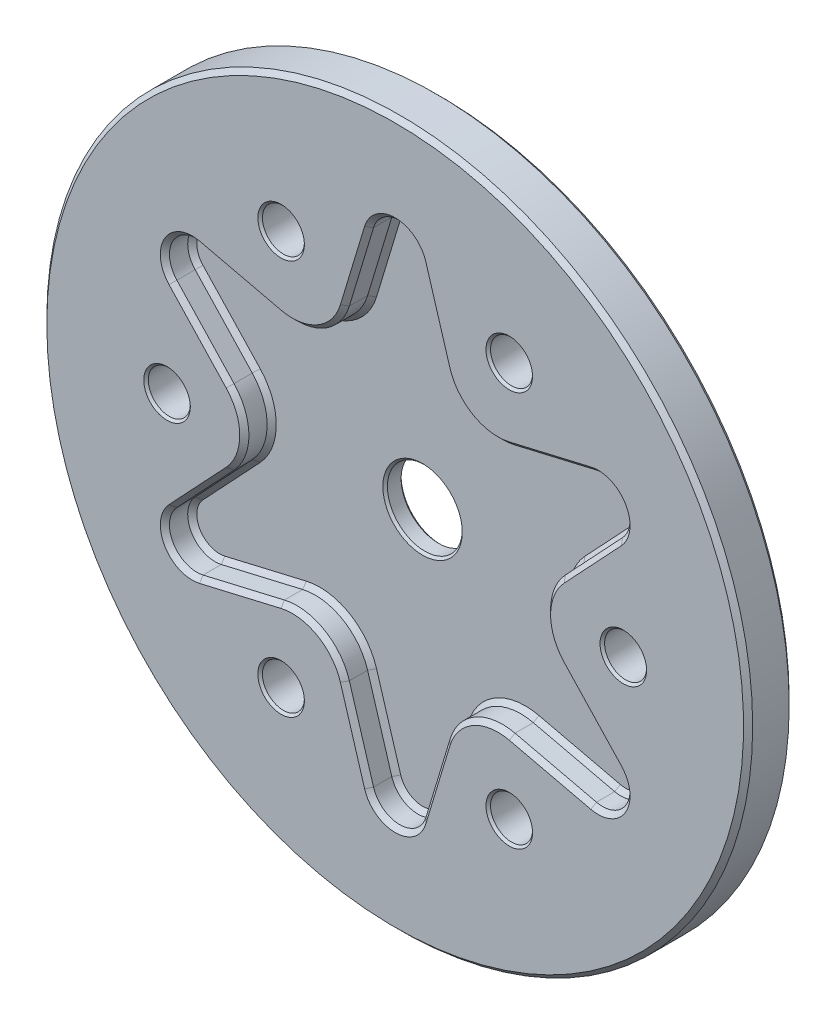
SolidWorks part; units mm, degrees
ref_plane "Front Plane" through (0, 0, 0) normal (0, 0, 1) x (1, 0, 0)
ref_plane "Top Plane" through (0, 0, 0) normal (0, 1, 0) x (1, 0, 0)
ref_plane "Right Plane" through (0, 0, 0) normal (1, 0, 0) x (0, 0, -1)
sketch "Sketch1" plane through (0, 0, 0) normal (0, 1, 0) x (1, 0, 0)
  line L0 (0, 0) -> (0, 5)
  line L4 (-38.675, 0) -> (-38.675, 5)
  line L5 (0, 5) -> (-38.675, 5)
  line L9 (-38.675, 0) -> (0, 0)
  dimension "D2" = 5
  dimension "D5" = 38.675
revolve "Revolve1" add sketch "Sketch1" angle 360 about L0
sketch "Sketch3" plane through (0, 0, 0) normal (0, 0, -1) x (-1, 0, 0)
  line L0 (25, 0) -> (-25, 0) construction
  circle A0 centre (0, 0) radius 4.1
  circle A3 centre (-12.5, 21.6506) radius 2.3
  circle A4 centre (12.5, 21.6506) radius 2.3
  circle A5 centre (25, 0) radius 2.3
  circle A6 centre (12.5, -21.6506) radius 2.3
  circle A7 centre (-12.5, -21.6506) radius 2.3
  circle A8 centre (-25, 0) radius 2.3
  point P0 (0, 0)
  dimension "D1" = 8.2
  dimension "D2" = 4.6
  dimension "D3" = 25
  dimension "D4" = 6
extrude "Cut-Extrude4" cut sketch "Sketch3" along normal through all
chamfer "Chamfer1" distance 0.5 angle 45 2 edges at (38.675, 0, 0) (38.675, 0, -5)
sketch "Sketch14" plane through (0, 0, 0) normal (0, 0, 1) x (1, 0, 0)
  line L0 (-2.8716, 26.5434) -> (-5.5228, 17.7764)
  line L1 (2.8716, 26.5434) -> (5.5228, 17.7764)
  line L2 (0, 0) -> (-12.5, 21.6506) construction
  line L3 (0, 0) -> (12.5, 21.6506) construction
  line L4 (0, 28.675) -> (0, 0) construction
  line L5 (21.5514, 15.7585) -> (12.6334, 13.671)
  line L6 (24.423, 10.7848) -> (18.1561, 4.1053)
  line L7 (24.423, -10.7848) -> (18.1561, -4.1053)
  line L8 (21.5514, -15.7585) -> (12.6334, -13.671)
  line L9 (2.8716, -26.5434) -> (5.5228, -17.7764)
  line L10 (-2.8716, -26.5434) -> (-5.5228, -17.7764)
  line L11 (-21.5514, -15.7585) -> (-12.6334, -13.671)
  line L12 (-24.423, -10.7848) -> (-18.1561, -4.1053)
  line L13 (-24.423, 10.7848) -> (-18.1561, 4.1053)
  line L14 (-21.5514, 15.7585) -> (-12.6334, 13.671)
  arc A0 (-2.8716, 26.5434) -> (2.8716, 26.5434) centre (0, 25.675) cw
  arc A1 (-5.5228, 17.7764) -> (-8.2659, 14.3169) centre (-11.2659, 19.5131) cw
  arc A2 (5.5228, 17.7764) -> (8.2659, 14.3169) centre (11.2659, 19.5131) ccw
  circle A4 centre (12.5, 21.6506) radius 2.3 construction
  circle A10 centre (0, 0) radius 38.675 construction
  arc A11 (12.6334, 13.671) -> (8.2659, 14.3169) centre (11.2659, 19.5131) cw
  arc A12 (21.5514, 15.7585) -> (24.423, 10.7848) centre (22.2352, 12.8375) cw
  arc A13 (18.1561, 4.1053) -> (16.5318, 0) centre (22.5318, 0) ccw
  arc A14 (18.1561, -4.1053) -> (16.5318, 0) centre (22.5318, 0) cw
  arc A15 (24.423, -10.7848) -> (21.5514, -15.7585) centre (22.2352, -12.8375) cw
  arc A16 (12.6334, -13.671) -> (8.2659, -14.3169) centre (11.2659, -19.5131) ccw
  arc A17 (5.5228, -17.7764) -> (8.2659, -14.3169) centre (11.2659, -19.5131) cw
  arc A18 (2.8716, -26.5434) -> (-2.8716, -26.5434) centre (0, -25.675) cw
  arc A19 (-5.5228, -17.7764) -> (-8.2659, -14.3169) centre (-11.2659, -19.5131) ccw
  arc A20 (-12.6334, -13.671) -> (-8.2659, -14.3169) centre (-11.2659, -19.5131) cw
  arc A21 (-21.5514, -15.7585) -> (-24.423, -10.7848) centre (-22.2352, -12.8375) cw
  arc A22 (-18.1561, -4.1053) -> (-16.5318, 0) centre (-22.5318, 0) ccw
  arc A23 (-18.1561, 4.1053) -> (-16.5318, 0) centre (-22.5318, 0) cw
  arc A24 (-24.423, 10.7848) -> (-21.5514, 15.7585) centre (-22.2352, 12.8375) cw
  arc A25 (-12.6334, 13.671) -> (-8.2659, 14.3169) centre (-11.2659, 19.5131) ccw
  point P67 (0, 0)
  dimension "D1" = 3
  dimension "D2" = 6
  dimension "D3" = 5.5
  dimension "D4" = 10
  dimension "D5" = 6
extrude "Cut-Extrude11" cut sketch "Sketch14" against normal blind 3
chamfer "Chamfer2" distance 0.5 angle 45 48 edges at (21.2896, -7.4451, 0) (16.5318, 0, 0) (24.8333, -14.3375, 0) (21.2896, 7.4451, 0) (17.0924, -14.7148, 0) (24.8333, 14.3375, 0) (8.2659, -14.3169, 0) (17.0924, 14.7148, 0) (4.1972, -22.1599, 0) (8.2659, 14.3169, 0) (0, -28.675, 0) (4.1972, 22.1599, 0) (-4.1972, -22.1599, 0) (0, 28.675, 0) (-8.2659, -14.3169, 0) (-4.1972, 22.1599, 0) (-17.0924, -14.7148, 0) (-8.2659, 14.3169, 0) (-24.8333, -14.3375, 0) (-17.0924, 14.7148, 0) (-21.2896, -7.4451, 0) (-24.8333, 14.3375, 0) (-16.5318, 0, 0) (-21.2896, 7.4451, 0) (8.2659, -14.3169, -3) (17.0924, -14.7148, -3) (4.1972, -22.1599, -3) (24.8333, -14.3375, -3) (0, -28.675, -3) (21.2896, -7.4451, -3) (-4.1972, -22.1599, -3) (16.5318, 0, -3) (-8.2659, -14.3169, -3) (21.2896, 7.4451, -3) (-17.0924, -14.7148, -3) (24.8333, 14.3375, -3) (-24.8333, -14.3375, -3) (17.0924, 14.7148, -3) (-21.2896, -7.4451, -3) (8.2659, 14.3169, -3) (-16.5318, 0, -3) (4.1972, 22.1599, -3) (-21.2896, 7.4451, -3) (0, 28.675, -3) (-24.8333, 14.3375, -3) (-4.1972, 22.1599, -3) (-17.0924, 14.7148, -3) (-8.2659, 14.3169, -3)
chamfer "Chamfer3" distance 0.25 angle 45 14 edges at (-4.1, 0, -5) (-4.1, 0, -3) (-14.8, -21.6506, 0) (-14.8, -21.6506, -5) (10.2, -21.6506, 0) (10.2, -21.6506, -5) (22.7, 0, 0) (22.7, 0, -5) (10.2, 21.6506, 0) (10.2, 21.6506, -5) (-14.8, 21.6506, 0) (-14.8, 21.6506, -5) (-27.3, 0, 0) (-27.3, 0, -5)
equation "\"pitch_diameter\"= \"teeth\" * \"pitch\" / pi"
equation "\"pitch\"= 0.5in"
equation "\"teeth\"= 17"
